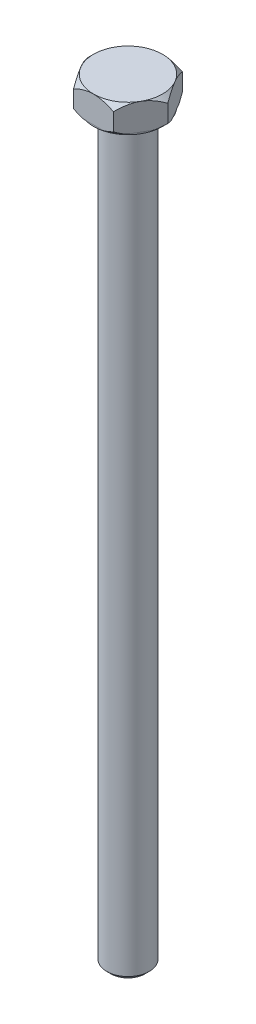
SolidWorks part; units mm, degrees
material "Cast Stainless Steel"
ref_plane "Front Plane" through (0, 0, 0) normal (0, 0, 1) x (1, 0, 0)
ref_plane "Top Plane" through (0, 0, 0) normal (0, 1, 0) x (1, 0, 0)
ref_plane "Right Plane" through (0, 0, 0) normal (1, 0, 0) x (0, 0, -1)
sketch "Sketch1" plane through (0, 0, 0) normal (0, 1, 0) x (1, 0, 0)
  line L0 (0, 0) -> (7.5056, 0) construction
  line L1 (7.5056, 0) -> (3.7528, 6.5)
  line L2 (3.7528, 6.5) -> (-3.7528, 6.5)
  line L3 (-3.7528, 6.5) -> (-7.5056, 0)
  line L4 (-7.5056, 0) -> (-3.7528, -6.5)
  line L5 (-3.7528, -6.5) -> (3.7528, -6.5)
  line L6 (3.7528, -6.5) -> (7.5056, 0)
  circle A0 centre (0, 0) radius 6.5 construction
  dimension "D1" = 13
extrude "Boss-Extrude1" add sketch "Sketch1" against normal blind 5.3
sketch "Sketch4" plane through (0, 0, 0) normal (1, 0, 0) x (0, 0, -1)
  line L0 (-6.5, 0) -> (-8.15, 0)
  line L1 (-8.15, 0) -> (-8.15, -1.65)
  line L2 (-8.15, -1.65) -> (-6.5, 0)
  line L3 (-6.5, -2.65) -> (6.5, -2.65) construction
  line L4 (-8.15, -3.65) -> (-6.5, -5.3)
  line L5 (-8.15, -5.3) -> (-8.15, -3.65)
  line L6 (-6.5, -5.3) -> (-8.15, -5.3)
  line L7 (0, 0) -> (0, -2.65) construction
  dimension "D1" = 45
  dimension "D2" = 2.65
  dimension "D3" = 1.65
  dimension "D4" = 13
revolve "Cut-Revolve1" cut sketch "Sketch4" angle 360 about L7
sketch "Sketch2" plane through (0, -5.3, 0) normal (0, -1, 0) x (1, 0, 0)
  circle A0 centre (0, 0) radius 6.5
  dimension "D1" = 13
extrude "Cut-Extrude1" cut sketch "Sketch2" against normal blind 0.265 flip side to cut
sketch "Sketch3" plane through (0, -5.3, 0) normal (0, -1, 0) x (1, 0, 0)
  circle A0 centre (0, 0) radius 4
  dimension "D1" = 8
extrude "Boss-Extrude2" add sketch "Sketch3" along normal blind 140
chamfer "Chamfer1" distance 0.8 angle 45 1 edges at (0, -145.3, -4)
equation "\"k\"= 5.3"
equation "\"e\"= 14.38"
equation "\"S\"= 13"
equation "\"L\"=140"
equation "\"D1@Sketch1\"=\"S\""
equation "\"D1@Boss-Extrude1\"=\"k\""
equation "\"D1@Sketch2\"=\"S\""
equation "\"D1@Cut-Extrude1\"=\"k\"/20"
equation "\"d\"= 8"
equation "\"D1@Sketch3\"=\"d\""
equation "\"D1@Boss-Extrude2\"=\"L\""
equation "\"D2@Sketch4\"=\"k\"/2"
equation "\"D3@Sketch4\"=\"D2@Sketch4\"-1"
equation "\"D4@Sketch4\"=\"S\""
equation "\"D1@Chamfer1\"=\"d\"/10"
